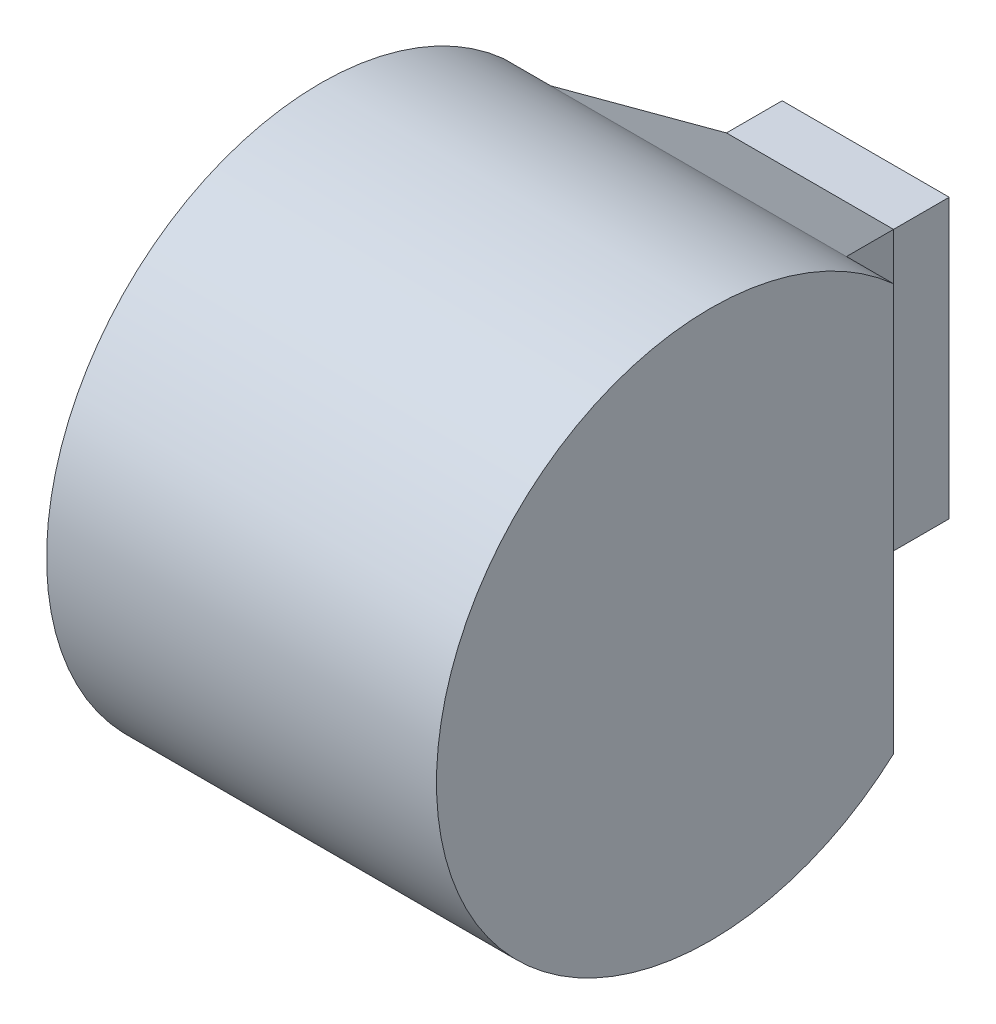
SolidWorks part; units mm, degrees
ref_plane "前视基准面" through (0, 0, 0) normal (0, 0, 1) x (1, 0, 0)
ref_plane "上视基准面" through (0, 0, 0) normal (0, 1, 0) x (1, 0, 0)
ref_plane "右视基准面" through (0, 0, 0) normal (1, 0, 0) x (0, 0, -1)
sketch "草图1" plane through (0, 0, 0) normal (0, 0, 1) x (1, 0, 0)
  line L1 (-15, 25) -> (15, 25)
  line L2 (-15, 25) -> (-15, -25)
  line L3 (-15, -25) -> (15, -25)
  line L4 (15, 25) -> (15, -25)
  line L5 (-15, 25) -> (15, -25) construction
  line L6 (-15, -25) -> (15, 25) construction
  point P0 (0, 0)
  dimension "D1" = 50
  dimension "D2" = 30
extrude "凸台-拉伸1" add sketch "草图1" along normal blind 10
sketch "草图2" plane through (0, 0, 10) normal (0, 0, 1) x (1, 0, 0)
  line L4 (15, -25) -> (15, 25)
  line L5 (15, 25) -> (-15, 25)
  line L6 (-15, 25) -> (-15, -25)
  line L7 (-15, -25) -> (15, -25)
  line L8 (15, -25) -> (15, 25)
  line L9 (15, 25) -> (-15, 25)
  line L10 (-15, 25) -> (-15, -25)
  line L11 (-15, -25) -> (15, -25)
  dimension "D1" = 0
extrude "凸台-拉伸2" add sketch "草图2" along normal blind 20 draft 30 draft outward yes
sketch "草图3" plane through (0, 0, 0) normal (1, 0, 0) x (0, 0, -1)
  line L0 (-30, 36.547) -> (-30, -36.547)
  arc A0 (-30, 36.547) -> (-30, -36.547) centre (-62.8939, 0) ccw
extrude "凸台-拉伸3" add sketch "草图3" along normal mid plane 70
